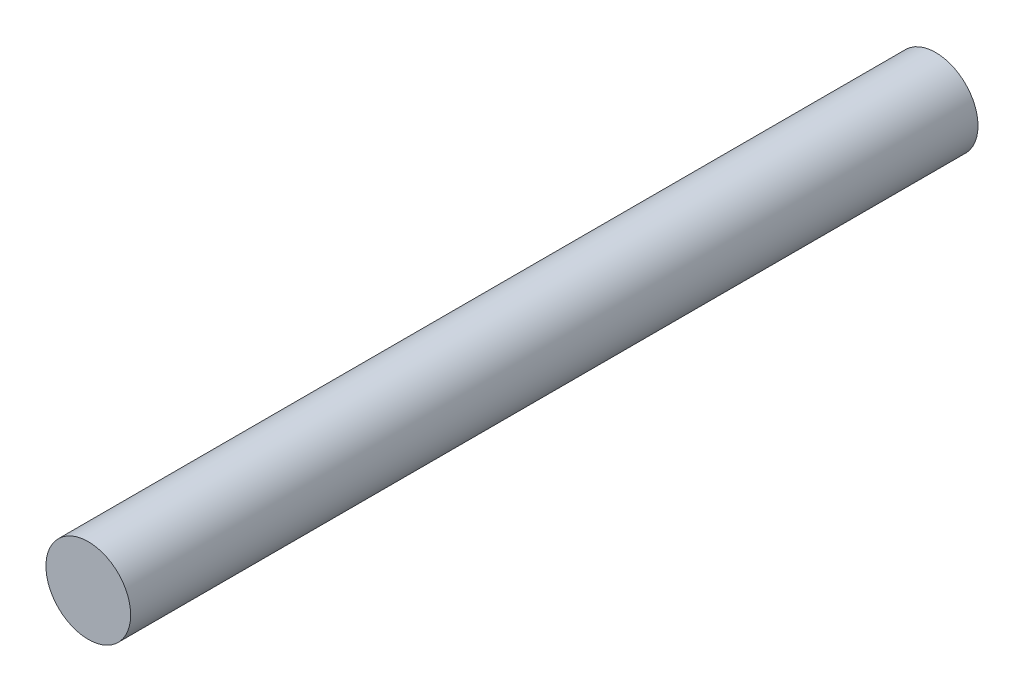
SolidWorks part; units mm, degrees
material "Custom Plastic"
ref_plane "Front Plane" through (0, 0, 0) normal (0, 0, 1) x (1, 0, 0)
ref_plane "Top Plane" through (0, 0, 0) normal (0, 1, 0) x (1, 0, 0)
ref_plane "Right Plane" through (0, 0, 0) normal (1, 0, 0) x (0, 0, -1)
other "Configuration Table"
sketch "Sketch1" plane through (0, 0, 0) normal (0, 0, 1) x (1, 0, 0)
  circle A0 centre (0, 0) radius 10
  dimension "D1" = 20
extrude "Boss-Extrude1" add sketch "Sketch1" along normal mid plane 200
